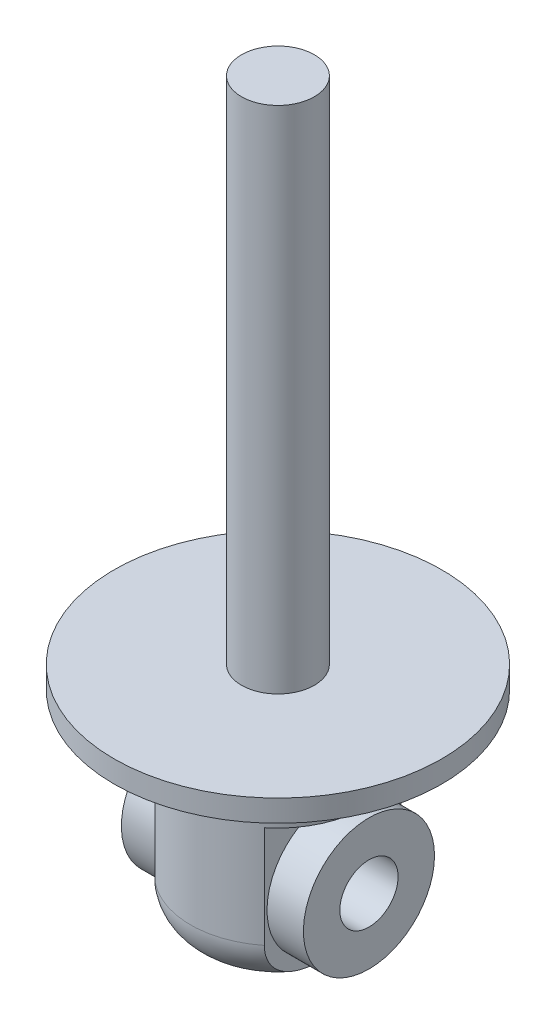
SolidWorks part; units mm, degrees
ref_plane "Front Plane" through (0, 0, 0) normal (0, 0, 1) x (1, 0, 0)
ref_plane "Top Plane" through (0, 0, 0) normal (0, 1, 0) x (1, 0, 0)
ref_plane "Right Plane" through (0, 0, 0) normal (1, 0, 0) x (0, 0, -1)
sketch "Sketch1" plane through (0, 0, 0) normal (0, 1, 0) x (1, 0, 0)
  circle A0 centre (0, 0) radius 22.5
  dimension "D1" = 45
extrude "Boss-Extrude1" add sketch "Sketch1" along normal blind 3
sketch "Sketch3" plane through (0, 3, 0) normal (0, 1, 0) x (1, 0, 0)
  circle A0 centre (0, 0) radius 5
  dimension "D1" = 10
extrude "Boss-Extrude2" add sketch "Sketch3" along normal blind 70
sketch "Sketch4" plane through (0, 0, 0) normal (0, -1, 0) x (1, 0, 0)
  circle A0 centre (0, 0) radius 12
  dimension "D1" = 24
extrude "Boss-Extrude3" add sketch "Sketch4" along normal blind 28
fillet "Fillet1" radius 6 1 edges at (0, -28, -12)
sketch "Sketch5" plane through (0, 0, 0) normal (0, 0, 1) x (1, 0, 0)
  line L0 (0, 0) -> (0, -28) construction
  line L1 (-6, -28) -> (6, -28) construction
  line L2 (7.5, -28) -> (27.07, -28)
  line L3 (27.07, -28) -> (27.07, -8)
  line L4 (27.07, -8) -> (7.5, -8)
  line L5 (7.5, -8) -> (7.5, -28)
  line L6 (-7.5, -8) -> (-7.5, -28)
  line L7 (-27.07, -8) -> (-7.5, -8)
  line L8 (-27.07, -28) -> (-27.07, -8)
  line L9 (-7.5, -28) -> (-27.07, -28)
  dimension "D1" = 15
  dimension "D2" = 20
  dimension "D3" = 19.57
extrude "Cut-Extrude1" cut sketch "Sketch5" against normal through all both and the other way through all
sketch "Sketch8" plane through (7.5, 0, 0) normal (1, 0, 0) x (0, 0, -1)
  line L0 (0, 0) -> (0, -28) construction
  line L1 (-6, -28) -> (6, -28) construction
  circle A0 centre (0, -18) radius 4
  dimension "D1" = 8
  dimension "D2" = 10
extrude "Cut-Extrude3" cut sketch "Sketch8" against normal blind 28
sketch "Sketch9" plane through (7.5, 0, 0) normal (1, 0, 0) x (0, 0, -1)
  circle A0 centre (0, -18) radius 9
  circle A2 centre (0, -18) radius 4
  circle A3 centre (0, -18) radius 4
  dimension "D1" = 18
  dimension "D2" = 0
sketch "Sketch10" plane through (0, 0, 0) normal (1, 0, 0) x (0, 0, -1)
  circle A1 centre (0, -18) radius 4
  circle A2 centre (0, -18) radius 4
  circle A3 centre (0, -18) radius 9
  circle A4 centre (0, -18) radius 9
  dimension "D1" = 0
  dimension "D2" = 0
extrude "Boss-Extrude4" add sketch "Sketch10" along normal mid plane 25
